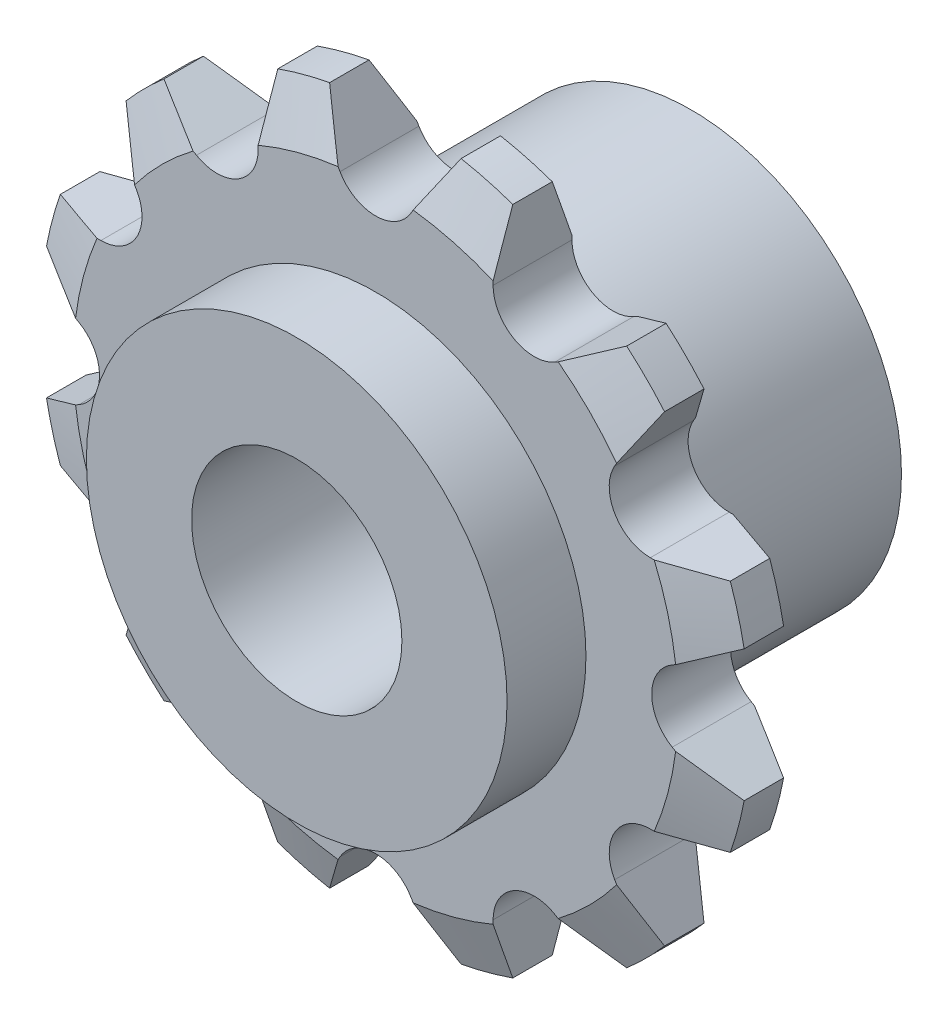
SolidWorks part; units mm, degrees
ref_plane "Front Plane" through (0, 0, 0) normal (0, 0, 1) x (1, 0, 0)
ref_plane "Top Plane" through (0, 0, 0) normal (0, 1, 0) x (1, 0, 0)
ref_plane "Right Plane" through (0, 0, 0) normal (1, 0, 0) x (0, 0, -1)
sketch "Sketch1" plane through (0, 0, 0) normal (0, 1, 0) x (1, 0, 0)
  line L0 (0, 0) -> (0, 15) construction
  line L1 (-4, 0) -> (-8, 0)
  line L2 (-8, 0) -> (-8, 3)
  line L3 (-8, 3) -> (-11.5, 3)
  line L4 (-13.5, 3.75) -> (-13.5, 5.25)
  line L5 (-11.5, 6) -> (-8, 6)
  line L6 (-8, 6) -> (-8, 15)
  line L7 (-8, 15) -> (-4, 15)
  line L8 (-4, 15) -> (-4, 0)
  line L9 (0, 0) -> (-4, 0) construction
  line L10 (-4, 15) -> (0, 15) construction
  line L11 (-13.25, 4.5) -> (0, 4.5) construction
  line L12 (-11.5, 6) -> (-13.5, 5.25)
  line L13 (-11.5, 3) -> (-13.5, 3.75)
  line L14 (-11.5, 6) -> (-13.5, 6) construction
  line L15 (-13.5, 6) -> (-13.5, 5.25) construction
  line L16 (-13.5, 3.75) -> (-13.5, 3) construction
  line L17 (-13.5, 3) -> (-11.5, 3) construction
  dimension "D1" = 15
  dimension "D2" = 8
  dimension "D3" = 3
  dimension "D4" = 3
  dimension "D5" = 4
  dimension "D6" = 13.5
  dimension "D7" = 11.5
  dimension "D8" = 1.5
revolve "Revolve1" add sketch "Sketch1" angle 360 about L0
sketch "Sketch2" plane through (0, 0, -3) normal (0, 0, 1) x (1, 0, 0)
  line L0 (0, 0) -> (0, 13.5) construction
  line L1 (-2.5, 13.2665) -> (-1.3541, 11.2818)
  line L2 (2.5, 13.2665) -> (1.3541, 11.2818)
  line L3 (4.4682, 12.7391) -> (4.4682, 10.4474)
  line L4 (8.7983, 10.2391) -> (6.8136, 9.0933)
  line L5 (10.2391, 8.7983) -> (9.0933, 6.8136)
  line L6 (12.7391, 4.4682) -> (10.4474, 4.4682)
  line L7 (13.2665, 2.5) -> (11.2818, 1.3541)
  line L8 (13.2665, -2.5) -> (11.2818, -1.3541)
  line L9 (12.7391, -4.4682) -> (10.4474, -4.4682)
  line L10 (10.2391, -8.7983) -> (9.0933, -6.8136)
  line L11 (8.7983, -10.2391) -> (6.8136, -9.0933)
  line L12 (4.4682, -12.7391) -> (4.4682, -10.4474)
  line L13 (2.5, -13.2665) -> (1.3541, -11.2818)
  line L14 (-2.5, -13.2665) -> (-1.3541, -11.2818)
  line L15 (-4.4682, -12.7391) -> (-4.4682, -10.4474)
  line L16 (-8.7983, -10.2391) -> (-6.8136, -9.0933)
  line L17 (-10.2391, -8.7983) -> (-9.0933, -6.8136)
  line L18 (-12.7391, -4.4682) -> (-10.4474, -4.4682)
  line L19 (-13.2665, -2.5) -> (-11.2818, -1.3541)
  line L20 (-13.2665, 2.5) -> (-11.2818, 1.3541)
  line L21 (-12.7391, 4.4682) -> (-10.4474, 4.4682)
  line L22 (-10.2391, 8.7983) -> (-9.0933, 6.8136)
  line L23 (-8.7983, 10.2391) -> (-6.8136, 9.0933)
  line L24 (-4.4682, 12.7391) -> (-4.4682, 10.4474)
  circle A0 centre (0, 0) radius 13.5 construction
  arc A1 (-4.4682, 12.7391) -> (-8.7983, 10.2391) centre (0, 0) ccw
  arc A2 (-1.3541, 11.2818) -> (1.3541, 11.2818) centre (0, 12.0636) ccw
  arc A3 (4.4682, 10.4474) -> (6.8136, 9.0933) centre (6.0318, 10.4474) ccw
  arc A4 (9.0933, 6.8136) -> (10.4474, 4.4682) centre (10.4474, 6.0318) ccw
  arc A5 (11.2818, 1.3541) -> (11.2818, -1.3541) centre (12.0636, 0) ccw
  arc A6 (10.4474, -4.4682) -> (9.0933, -6.8136) centre (10.4474, -6.0318) ccw
  arc A7 (6.8136, -9.0933) -> (4.4682, -10.4474) centre (6.0318, -10.4474) ccw
  arc A8 (1.3541, -11.2818) -> (-1.3541, -11.2818) centre (0, -12.0636) ccw
  arc A9 (-4.4682, -10.4474) -> (-6.8136, -9.0933) centre (-6.0318, -10.4474) ccw
  arc A10 (-9.0933, -6.8136) -> (-10.4474, -4.4682) centre (-10.4474, -6.0318) ccw
  arc A11 (-11.2818, -1.3541) -> (-11.2818, 1.3541) centre (-12.0636, 0) ccw
  arc A12 (-10.4474, 4.4682) -> (-9.0933, 6.8136) centre (-10.4474, 6.0318) ccw
  arc A13 (-6.8136, 9.0933) -> (-4.4682, 10.4474) centre (-6.0318, 10.4474) ccw
  arc A14 (-10.2391, 8.7983) -> (-12.7391, 4.4682) centre (0, 0) ccw
  arc A15 (-13.2665, 2.5) -> (-13.2665, -2.5) centre (0, 0) ccw
  arc A16 (-12.7391, -4.4682) -> (-10.2391, -8.7983) centre (0, 0) ccw
  arc A17 (-8.7983, -10.2391) -> (-4.4682, -12.7391) centre (0, 0) ccw
  arc A18 (-2.5, -13.2665) -> (2.5, -13.2665) centre (0, 0) ccw
  arc A19 (4.4682, -12.7391) -> (8.7983, -10.2391) centre (0, 0) ccw
  arc A20 (10.2391, -8.7983) -> (12.7391, -4.4682) centre (0, 0) ccw
  arc A21 (13.2665, -2.5) -> (13.2665, 2.5) centre (0, 0) ccw
  arc A22 (12.7391, 4.4682) -> (10.2391, 8.7983) centre (0, 0) ccw
  arc A23 (8.7983, 10.2391) -> (4.4682, 12.7391) centre (0, 0) ccw
  arc A24 (-2.5, 13.2665) -> (2.5, 13.2665) centre (0, 0) cw
  point P7 (0, 10.5)
  point P67 (0, 0)
  dimension "D1" = 10.5
  dimension "D2" = 5
  dimension "D3" = 60
  dimension "D4" = 12
extrude "Cut-Extrude1" cut sketch "Sketch2" against normal through all
